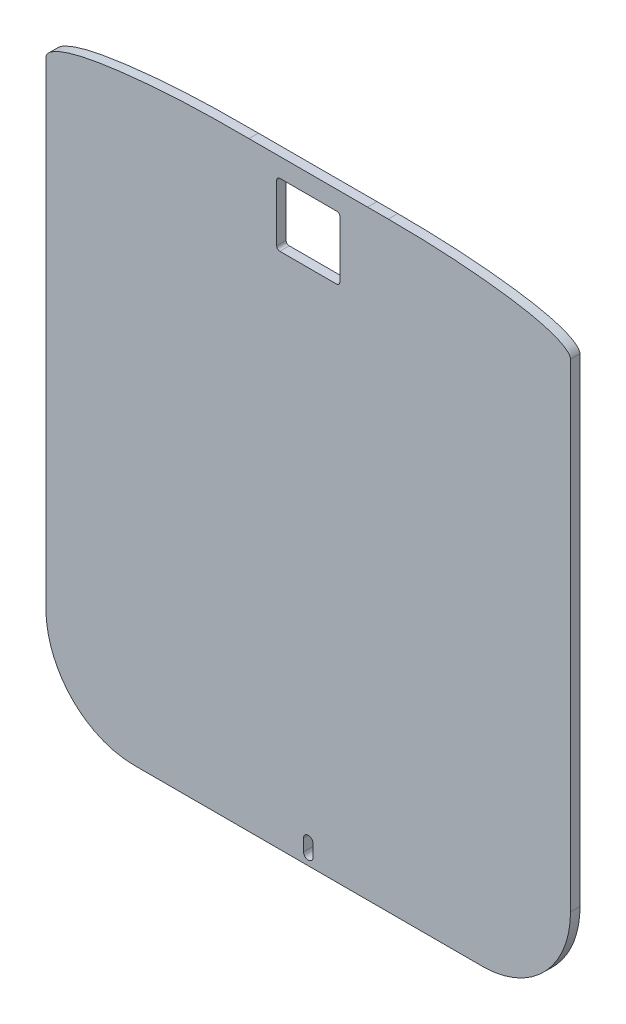
SolidWorks part; units mm, degrees
material "Beech"
ref_plane "Front Plane" through (0, 0, 0) normal (0, 0, 1) x (1, 0, 0)
ref_plane "Top Plane" through (0, 0, 0) normal (0, 1, 0) x (1, 0, 0)
ref_plane "Right Plane" through (0, 0, 0) normal (1, 0, 0) x (0, 0, -1)
sketch "Sketch1" plane through (0, 0, 0) normal (0, 0, 1) x (1, 0, 0)
  line L0 (-83, 132.5) -> (-83, -72.5)
  line L1 (-83, -72.5) -> (83, -72.5)
  line L2 (83, -72.5) -> (83, 132.5)
  line L3 (83, 132.5) -> (-83, 132.5)
  line L4 (80, -72.5) -> (80, 72.5)
  line L5 (80, 72.5) -> (-80, 72.5)
  line L6 (-80, 72.5) -> (-80, -72.5)
  line L7 (-80, -72.5) -> (80, -72.5)
  line L8 (80, -72.5) -> (80, 72.5) construction
  line L9 (80, 72.5) -> (-80, 72.5) construction
  line L10 (-80, 72.5) -> (-80, -72.5) construction
  line L11 (-80, -72.5) -> (80, -72.5) construction
  line L12 (0, 132.5) -> (0, -72.5) construction
  line L15 (0, -63.5748) -> (0, -67.368) construction
  line L16 (1.5, -63.5748) -> (1.5, -67.368)
  line L17 (-1.5, -63.5748) -> (-1.5, -67.368)
  arc A1 (1.5, -63.5748) -> (-1.5, -63.5748) centre (0, -63.5748) ccw
  arc A2 (-1.5, -67.368) -> (1.5, -67.368) centre (0, -67.368) ccw
  point P6 (0, -65.4714)
  dimension "D4" = 3
  dimension "D2" = 60
  dimension "D3" = 3
  dimension "D1" = 0
extrude "Boss-Extrude1" add sketch "Sketch1" along normal blind 3
sketch "Sketch2" plane through (0, 0, 3) normal (0, 0, 1) x (1, 0, 0)
  line L0 (83, -41.5617) -> (82.9838, 109.9214)
  line L1 (83, -41.5617) -> (82.9838, 109.9214)
  line L4 (-83, -41.5617) -> (-83, 109.765)
  line L5 (-83, -41.5617) -> (-83, 109.765)
  line L6 (55.1094, -70.4332) -> (-55.1094, -70.4332)
  line L7 (55.1094, -70.4332) -> (-55.1094, -70.4332)
  line L8 (-18.7749, 119.5) -> (18.7749, 119.5)
  line L9 (-18.7749, 119.5) -> (18.7749, 119.5)
  line L12 (10, 94.5) -> (10, 112.5)
  line L13 (-9, 93.5) -> (9, 93.5)
  line L14 (-10, 112.5) -> (-10, 94.5)
  line L15 (9, 113.5) -> (-9, 113.5)
  line L16 (10, 94.5) -> (10, 112.5)
  line L17 (-9, 93.5) -> (9, 93.5)
  line L18 (-10, 112.5) -> (-10, 94.5)
  line L19 (9, 113.5) -> (-9, 113.5)
  arc A4 (10, 112.5) -> (9, 113.5) centre (9, 112.5) ccw
  arc A5 (9, 93.5) -> (10, 94.5) centre (9, 94.5) ccw
  arc A6 (-10, 94.5) -> (-9, 93.5) centre (-9, 94.5) ccw
  arc A7 (-9, 113.5) -> (-10, 112.5) centre (-9, 112.5) ccw
  arc A8 (10, 112.5) -> (9, 113.5) centre (9, 112.5) ccw
  arc A9 (9, 93.5) -> (10, 94.5) centre (9, 94.5) ccw
  arc A10 (-10, 94.5) -> (-9, 93.5) centre (-9, 94.5) ccw
  arc A11 (-9, 113.5) -> (-10, 112.5) centre (-9, 112.5) ccw
  spline S0 degree 3 poles (147.8218, 1105.5213) (108.2292, 108.7687) (42.5143, 119.533) (-24.3026, 119.5023) (-25.6844, 119.4975) (-29.8293, 119.4619) (-32.5918, 119.4096) (-38.1149, 119.2312) (-40.8755, 119.1054) (-46.3945, 118.773) (-49.1526, 118.5662) (-54.6574, 118.0663) (-57.4055, 117.7757) (-62.8905, 117.0872) (-65.6294, 116.6881) (-69.708, 115.9316) (-71.0635, 115.6525) (-73.7542, 115.0129) (-75.0914, 114.6533) (-77.0628, 114.0083) (-77.7144, 113.7753) (-78.9971, 113.2566) (-79.6284, 112.9716) (-80.5419, 112.4798) (-80.8397, 112.3055) (-81.416, 111.9271) (-81.6955, 111.7228) (-82.0881, 111.3808) (-82.2137, 111.2616) (-82.4501, 111.0082) (-82.5615, 110.8733) (-82.7558, 110.5888) (-82.8394, 110.4391) (-82.9311, 110.1958) (-82.9559, 110.1107) (-86.3475, 92.798) (223.1221, 31.5779) (-1079.183, 197.0099) knots -2.896948 -2.896948 -2.896948 -2.896948 0.0625 0.0625 0.125 0.125 0.25 0.25 0.375 0.375 0.5 0.5 0.625 0.625 0.75 0.75 0.8125 0.8125 0.875 0.875 0.90625 0.90625 0.9375 0.9375 0.953125 0.953125 0.96875 0.96875 0.976562 0.976562 0.984375 0.984375 0.992187 0.992187 0.996094 0.996094 1.782054 1.782054 1.782054 1.782054 only from (-18.7749, 119.5) to (-83, 109.765)
  spline S1 degree 3 poles (-18.7749, 119.5) (-20.1568, 119.4994) (-21.5388, 119.5036) (-24.3026, 119.5023) (-25.6844, 119.4975) (-29.8293, 119.4619) (-32.5918, 119.4096) (-38.1149, 119.2312) (-40.8755, 119.1054) (-46.3945, 118.773) (-49.1526, 118.5662) (-54.6574, 118.0663) (-57.4055, 117.7757) (-62.8905, 117.0872) (-65.6294, 116.6881) (-69.708, 115.9316) (-71.0635, 115.6525) (-73.7542, 115.0129) (-75.0914, 114.6533) (-77.0628, 114.0083) (-77.7144, 113.7753) (-78.9971, 113.2566) (-79.6284, 112.9716) (-80.5419, 112.4798) (-80.8397, 112.3055) (-81.416, 111.9271) (-81.6955, 111.7228) (-82.0881, 111.3808) (-82.2137, 111.2616) (-82.4501, 111.0082) (-82.5615, 110.8733) (-82.7558, 110.5888) (-82.8394, 110.4391) (-82.9311, 110.1958) (-82.9559, 110.1107) (-82.9894, 109.9394) (-82.9984, 109.8527) (-83, 109.765) knots 0 0 0 0 0.0625 0.0625 0.125 0.125 0.25 0.25 0.375 0.375 0.5 0.5 0.625 0.625 0.75 0.75 0.8125 0.8125 0.875 0.875 0.90625 0.90625 0.9375 0.9375 0.953125 0.953125 0.96875 0.96875 0.976562 0.976562 0.984375 0.984375 0.992187 0.992187 0.996094 0.996094 1 1 1 1
  spline S2 degree 3 poles (-892.1701, -111.5186) (-48.9625, 60.8478) (86.6923, 98.8573) (82.8585, 110.5399) (82.7866, 110.6833) (82.6194, 110.9513) (82.5225, 111.0784) (82.3148, 111.3183) (82.2043, 111.4308) (81.8589, 111.7528) (81.6099, 111.9473) (81.0908, 112.3102) (80.8239, 112.476) (80.0088, 112.9424) (79.4463, 113.2124) (78.2996, 113.7061) (77.7151, 113.929) (76.5308, 114.3423) (75.9328, 114.5319) (74.7345, 114.8846) (74.1332, 115.048) (72.3239, 115.5087) (71.1109, 115.777) (67.4588, 116.5066) (65.0068, 116.8939) (60.0845, 117.5644) (57.6139, 117.8461) (50.1851, 118.5925) (45.2199, 118.9451) (37.7622, 119.2841) (35.2739, 119.3655) (-95.5755, 122.1568) (-224.6639, 48.4656) (-343.5348, 1048.9846) knots -0.588208 -0.588208 -0.588208 -0.588208 0.007812 0.007812 0.015625 0.015625 0.023437 0.023437 0.03125 0.03125 0.046875 0.046875 0.0625 0.0625 0.09375 0.09375 0.125 0.125 0.15625 0.15625 0.1875 0.1875 0.25 0.25 0.375 0.375 0.5 0.5 0.75 0.75 0.875 0.875 7.32374 7.32374 7.32374 7.32374 only from (82.9838, 109.9214) to (25.3207, 119.5)
  spline S3 degree 3 poles (944.6022, 497.4457) (-1036.3955, -403.0419) (910.9892, 841.5128) (-52.2173, -877.4812) knots -22.458803 -22.458803 -22.458803 -22.458803 31.822875 31.822875 31.822875 31.822875 only from (18.7749, 119.5) to (25.3207, 119.5)
  spline S4 degree 3 poles (850.1743, 317.8553) (120.5688, 125.5313) (-95.0672, 19.9571) (-82.3152, -48.0061) (-82.1026, -48.9073) (-81.5908, -50.6953) (-81.2897, -51.5864) (-80.2696, -54.1892) (-79.435, -55.8385) (-77.9518, -58.1839) (-77.4187, -58.9442) (-76.5583, -60.0509) (-76.261, -60.4146) (-75.6527, -61.1223) (-75.3409, -61.4675) (-73.7446, -63.15) (-72.3484, -64.3591) (-70.4512, -65.6959) (-70.0641, -65.9544) (-69.2742, -66.4534) (-68.8706, -66.6943) (-67.6499, -67.3813) (-66.8189, -67.7946) (-64.2755, -68.9037) (-62.5133, -69.4697) (-60.2233, -69.9506) (-59.7614, -70.0352) (-58.8373, -70.1798) (-58.3741, -70.2401) (8.454, -77.1805) (98.5402, 160.6452) (235.9126, 886.2695) knots -4.488635 -4.488635 -4.488635 -4.488635 0.125 0.125 0.1875 0.1875 0.25 0.25 0.375 0.375 0.4375 0.4375 0.46875 0.46875 0.5 0.5 0.625 0.625 0.65625 0.65625 0.6875 0.6875 0.75 0.75 0.875 0.875 0.90625 0.90625 0.9375 0.9375 5.403291 5.403291 5.403291 5.403291 only from (-83, -41.5617) to (-55.1094, -70.4332)
  spline S5 degree 3 poles (-83, -41.5617) (-82.9999, -43.4359) (-82.8265, -45.281) (-82.3152, -48.0061) (-82.1026, -48.9073) (-81.5908, -50.6953) (-81.2897, -51.5864) (-80.2696, -54.1892) (-79.435, -55.8385) (-77.9518, -58.1839) (-77.4187, -58.9442) (-76.5583, -60.0509) (-76.261, -60.4146) (-75.6527, -61.1223) (-75.3409, -61.4675) (-73.7446, -63.15) (-72.3484, -64.3591) (-70.4512, -65.6959) (-70.0641, -65.9544) (-69.2742, -66.4534) (-68.8706, -66.6943) (-67.6499, -67.3813) (-66.8189, -67.7946) (-64.2755, -68.9037) (-62.5133, -69.4697) (-60.2233, -69.9506) (-59.7614, -70.0352) (-58.8373, -70.1798) (-58.3741, -70.2401) (-56.9809, -70.3847) (-56.0475, -70.4333) (-55.1094, -70.4332) knots 0 0 0 0 0.125 0.125 0.1875 0.1875 0.25 0.25 0.375 0.375 0.4375 0.4375 0.46875 0.46875 0.5 0.5 0.625 0.625 0.65625 0.65625 0.6875 0.6875 0.75 0.75 0.875 0.875 0.90625 0.90625 0.9375 0.9375 1 1 1 1
  spline S6 degree 3 poles (-292.4479, 867.2224) (-100.5141, 120.9902) (-1.3994, -82.7843) (61.5421, -69.6752) (62.4394, -69.4402) (63.7731, -69.0163) (64.2168, -68.8625) (65.0916, -68.534) (65.5231, -68.3592) (67.6519, -67.4332) (69.2638, -66.5279) (71.5467, -64.9262) (72.2886, -64.3479) (73.6992, -63.1301) (75.0405, -61.8498) (76.2476, -60.4483) (77.3877, -58.9863) (77.9253, -58.2236) (79.429, -55.8523) (80.2641, -54.1991) (81.2787, -51.6165) (81.577, -50.7384) (82.0925, -48.9472) (82.3095, -48.0331) (96.7483, 28.6326) (-182.7888, 140.5802) (-856.4615, 301.0862) knots -4.15817 -4.15817 -4.15817 -4.15817 0.125 0.125 0.1875 0.1875 0.21875 0.21875 0.25 0.25 0.375 0.375 0.4375 0.4375 0.5 0.5625 0.5625 0.625 0.625 0.75 0.75 0.8125 0.8125 0.875 0.875 6.046901 6.046901 6.046901 6.046901 only from (55.1094, -70.4332) to (83, -41.5617)
  spline S7 degree 3 poles (55.1094, -70.4332) (56.9844, -70.4333) (58.8264, -70.2408) (61.5421, -69.6752) (62.4394, -69.4402) (63.7731, -69.0163) (64.2168, -68.8625) (65.0916, -68.534) (65.5231, -68.3592) (67.6519, -67.4332) (69.2638, -66.5279) (71.5467, -64.9262) (72.2886, -64.3479) (73.6992, -63.1301) (75.0405, -61.8498) (76.2476, -60.4483) (77.3877, -58.9863) (77.9253, -58.2236) (79.429, -55.8523) (80.2641, -54.1991) (81.2787, -51.6165) (81.577, -50.7384) (82.0925, -48.9472) (82.3095, -48.0331) (82.8267, -45.2869) (82.9999, -43.4349) (83, -41.5617) knots 0 0 0 0 0.125 0.125 0.1875 0.1875 0.21875 0.21875 0.25 0.25 0.375 0.375 0.4375 0.4375 0.5 0.5625 0.5625 0.625 0.625 0.75 0.75 0.8125 0.8125 0.875 0.875 1 1 1 1
  spline S8 degree 3 poles (18.7749, 119.5) (20.5982, 119.5) (22.7944, 119.5106) (25.3207, 119.5) knots 0 0 0 0 1 1 1 1
  spline S9 degree 3 poles (82.9838, 109.9214) (82.9834, 110.0819) (82.9577, 110.2376) (82.8585, 110.5399) (82.7866, 110.6833) (82.6194, 110.9513) (82.5225, 111.0784) (82.3148, 111.3183) (82.2043, 111.4308) (81.8589, 111.7528) (81.6099, 111.9473) (81.0908, 112.3102) (80.8239, 112.476) (80.0088, 112.9424) (79.4463, 113.2124) (78.2996, 113.7061) (77.7151, 113.929) (76.5308, 114.3423) (75.9328, 114.5319) (74.7345, 114.8846) (74.1332, 115.048) (72.3239, 115.5087) (71.1109, 115.777) (67.4588, 116.5066) (65.0068, 116.8939) (60.0845, 117.5644) (57.6139, 117.8461) (50.1851, 118.5925) (45.2199, 118.9451) (37.7622, 119.2841) (35.2739, 119.3655) (30.2977, 119.4716) (27.8093, 119.496) (25.3207, 119.5) knots 0 0 0 0 0.007812 0.007812 0.015625 0.015625 0.023437 0.023437 0.03125 0.03125 0.046875 0.046875 0.0625 0.0625 0.09375 0.09375 0.125 0.125 0.15625 0.15625 0.1875 0.1875 0.25 0.25 0.375 0.375 0.5 0.5 0.75 0.75 0.875 0.875 1 1 1 1
  dimension "D1" = 0
extrude "Cut-Extrude2" cut sketch "Sketch2" against normal blind 10 and the other way through all flip side to cut
sketch "Sketch3" plane through (0, 0, 3) normal (0, 0, 1) x (1, 0, 0)
  line L4 (10, 94.5) -> (10, 112.5)
  line L5 (-9, 93.5) -> (9, 93.5)
  line L6 (-10, 112.5) -> (-10, 94.5)
  line L7 (9, 113.5) -> (-9, 113.5)
  line L8 (10, 94.5) -> (10, 112.5)
  line L9 (-9, 93.5) -> (9, 93.5)
  line L10 (-10, 112.5) -> (-10, 94.5)
  line L11 (9, 113.5) -> (-9, 113.5)
  arc A4 (10, 112.5) -> (9, 113.5) centre (9, 112.5) ccw
  arc A5 (9, 93.5) -> (10, 94.5) centre (9, 94.5) ccw
  arc A6 (-10, 94.5) -> (-9, 93.5) centre (-9, 94.5) ccw
  arc A7 (-9, 113.5) -> (-10, 112.5) centre (-9, 112.5) ccw
  arc A8 (10, 112.5) -> (9, 113.5) centre (9, 112.5) ccw
  arc A9 (9, 93.5) -> (10, 94.5) centre (9, 94.5) ccw
  arc A10 (-10, 94.5) -> (-9, 93.5) centre (-9, 94.5) ccw
  arc A11 (-9, 113.5) -> (-10, 112.5) centre (-9, 112.5) ccw
  dimension "D1" = 0
extrude "Cut-Extrude3" cut sketch "Sketch3" against normal blind 10
